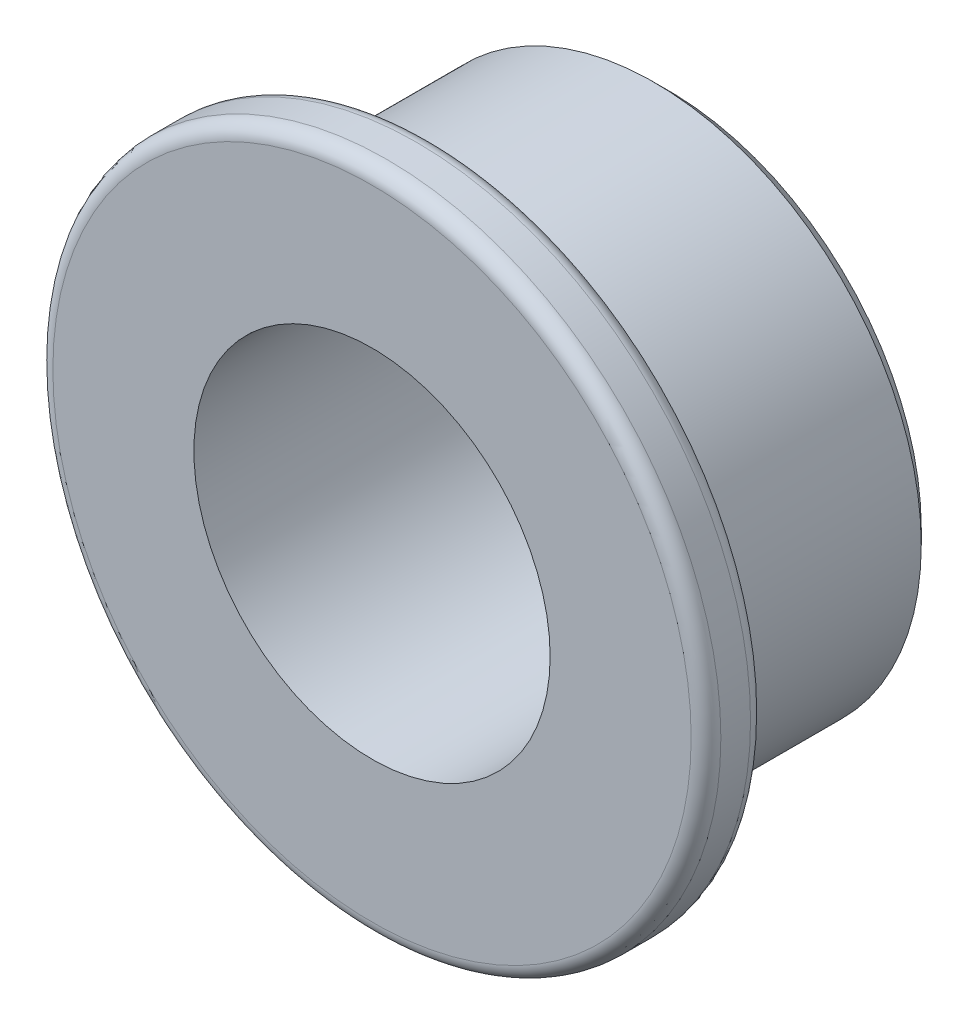
SolidWorks part; units mm, degrees
ref_plane "Front Plane" through (0, 0, 0) normal (0, 0, 1) x (1, 0, 0)
ref_plane "Top Plane" through (0, 0, 0) normal (0, 1, 0) x (1, 0, 0)
ref_plane "Right Plane" through (0, 0, 0) normal (1, 0, 0) x (0, 0, -1)
sketch "Sketch1" plane through (0, 0, 0) normal (0, 0, 1) x (1, 0, 0)
  circle A0 centre (0, 0) radius 9
  circle A1 centre (0, 0) radius 6
  dimension "D1" = 18
  dimension "D2" = 12
extrude "Boss-Extrude1" add sketch "Sketch1" against normal blind 8
sketch "Sketch2" plane through (0, 0, 0) normal (0, 0, 1) x (1, 0, 0)
  circle A0 centre (0, 0) radius 11.25
  circle A1 centre (0, 0) radius 6
  circle A2 centre (0, 0) radius 6 construction
  dimension "D1" = 22.5
extrude "Boss-Extrude2" add sketch "Sketch2" along normal blind 2
fillet "Fillet1" radius 0.5 1 edges at (11.25, 0, 2)
fillet "Fillet2" radius 0.5 1 edges at (11.25, 0, 0)
fillet "Fillet3" radius 0.8 1 edges at (9, 0, 0)
chamfer "Chamfer1" distance 0.5 angle 45 1 edges at (9, 0, -8)
